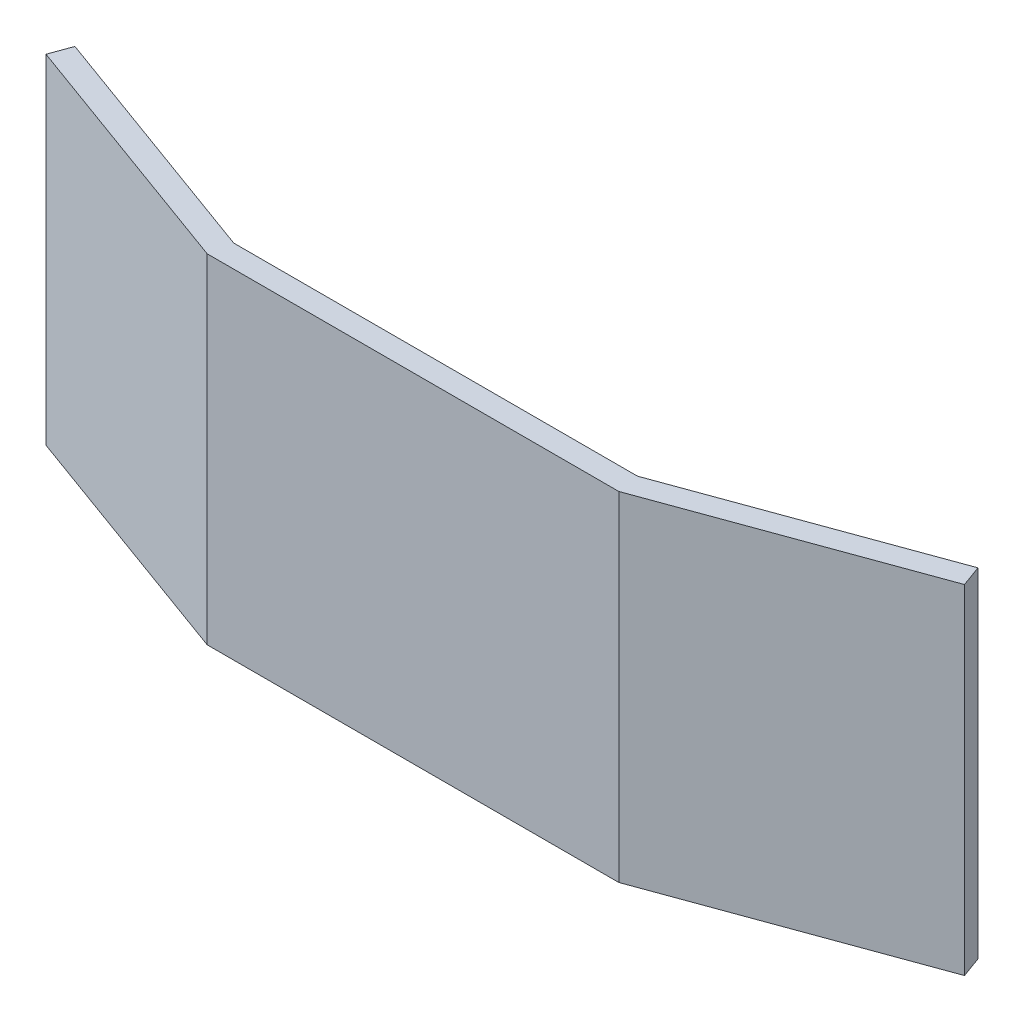
SolidWorks part; units mm, degrees
ref_plane "Front Plane" through (0, 0, 0) normal (0, 0, 1) x (1, 0, 0)
ref_plane "Top Plane" through (0, 0, 0) normal (0, 1, 0) x (1, 0, 0)
ref_plane "Right Plane" through (0, 0, 0) normal (1, 0, 0) x (0, 0, -1)
sketch "Sketch5" plane through (0, 0, 0) normal (0, 1, 0) x (1, 0, 0)
  line L12 (-40.684, 8.1715) -> (-18.2331, 0)
  line L13 (-40, 10.0509) -> (-40.684, 8.1715)
  line L14 (-18.2331, 0) -> (18.2331, 0)
  line L15 (18.2331, 0) -> (40.684, 8.1715)
  line L16 (40.684, 8.1715) -> (40, 10.0509)
  line L17 (40, 10.0509) -> (17.8804, 2)
  line L18 (-40, 10.0509) -> (-17.8804, 2)
  line L19 (-17.8804, 2) -> (17.8804, 2)
  point P8 (0, 0)
  dimension "D1" = 2
  dimension "D2" = 2
  dimension "D3" = 2
  dimension "D4" = 23.5392
  dimension "D5" = 23.8918
  dimension "D6" = 23.5392
  dimension "D7" = 23.8918
  dimension "D8" = 36.4661
extrude "Boss-Extrude1" add sketch "Sketch5" along normal blind 30
